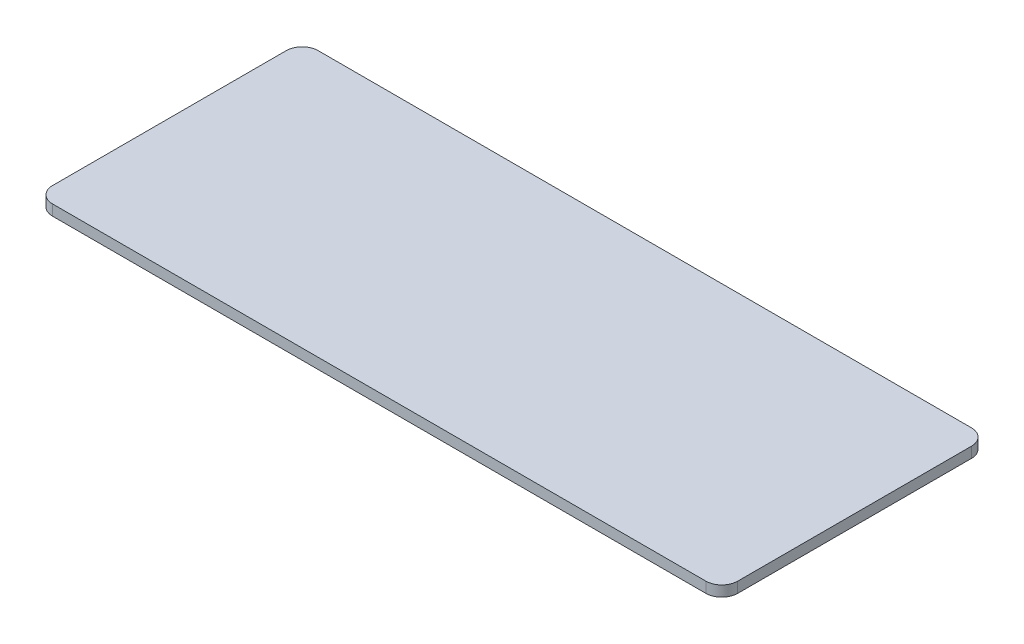
SolidWorks part; units mm, degrees
ref_plane "Front Plane" through (0, 0, 0) normal (0, 0, 1) x (1, 0, 0)
ref_plane "Top Plane" through (0, 0, 0) normal (0, 1, 0) x (1, 0, 0)
ref_plane "Right Plane" through (0, 0, 0) normal (1, 0, 0) x (0, 0, -1)
sketch "Sketch1" plane through (0, 0, 0) normal (0, 1, 0) x (1, 0, 0)
  line L1 (-64.5, -25) -> (64.5, -25)
  line L2 (-64.5, -25) -> (-64.5, 25)
  line L3 (-64.5, 25) -> (64.5, 25)
  line L4 (64.5, -25) -> (64.5, 25)
  line L5 (-64.5, -25) -> (64.5, 25) construction
  line L6 (-64.5, 25) -> (64.5, -25) construction
  point P0 (0, 0)
  dimension "D1" = 129
  dimension "D2" = 50
extrude "Boss-Extrude1" add sketch "Sketch1" along normal blind 2
fillet "Fillet1" radius 3 4 edges at (-64.5, 1, -25) (64.5, 1, -25) (64.5, 1, 25) (-64.5, 1, 25)
